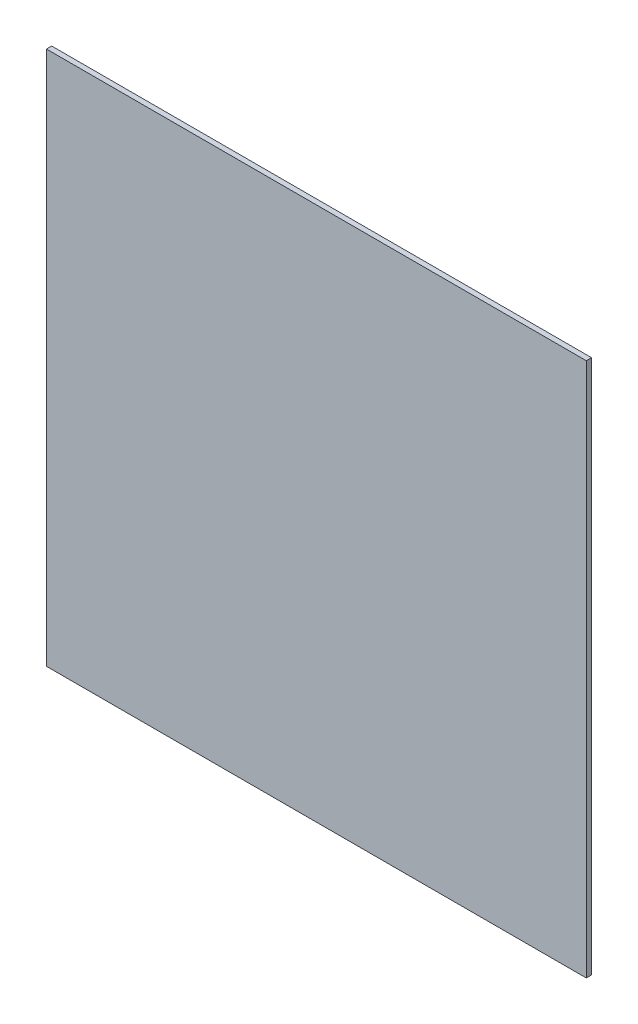
SolidWorks part; units mm, degrees
ref_plane "前视基准面" through (0, 0, 0) normal (0, 0, 1) x (1, 0, 0)
ref_plane "上视基准面" through (0, 0, 0) normal (0, 1, 0) x (1, 0, 0)
ref_plane "右视基准面" through (0, 0, 0) normal (1, 0, 0) x (0, 0, -1)
sketch "草图1" plane through (0, 0, 0) normal (0, 0, 1) x (1, 0, 0)
  line L1 (0, 0) -> (-103, 0)
  line L2 (0, 0) -> (0, 102)
  line L3 (0, 102) -> (-103, 102)
  line L4 (-103, 0) -> (-103, 102)
extrude "凸台-拉伸1" add sketch "草图1" along normal blind 1
